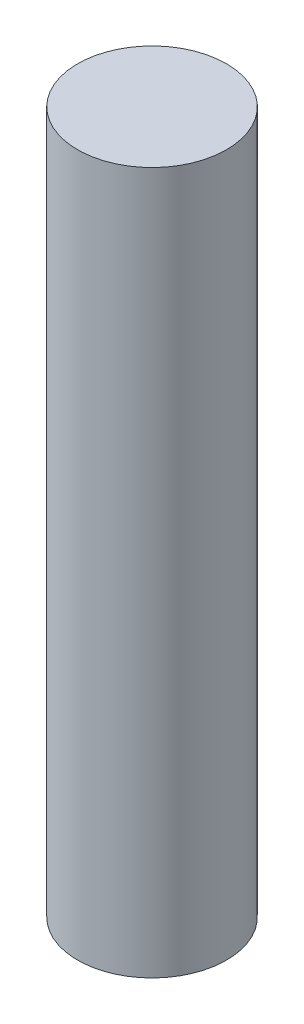
SolidWorks part; units mm, degrees
ref_plane "Front Plane" through (0, 0, 0) normal (0, 0, 1) x (1, 0, 0)
ref_plane "Top Plane" through (0, 0, 0) normal (0, 1, 0) x (1, 0, 0)
ref_plane "Right Plane" through (0, 0, 0) normal (1, 0, 0) x (0, 0, -1)
sketch "Sketch1" plane through (0, 0, 0) normal (0, 1, 0) x (1, 0, 0)
  circle A0 centre (0, 0) radius 4.775
  dimension "D1" = 9.55
extrude "Boss-Extrude1" add sketch "Sketch1" along normal blind 45
